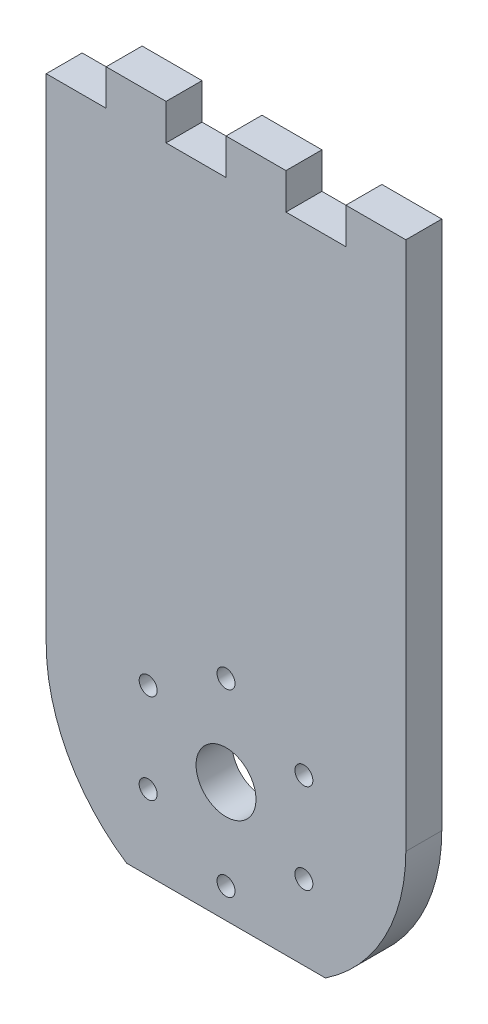
SolidWorks part; units mm, degrees
ref_plane "Alzado" through (0, 0, 0) normal (0, 0, 1) x (1, 0, 0)
ref_plane "Planta" through (0, 0, 0) normal (0, 1, 0) x (1, 0, 0)
ref_plane "Vista lateral" through (0, 0, 0) normal (1, 0, 0) x (0, 0, -1)
sketch "Croquis1" plane through (0, 0, 0) normal (0, 0, 1) x (1, 0, 0)
  line L0 (0, 28.345) -> (0, -18.345) construction
  line L1 (-15, -28.345) -> (15, -28.345)
  line L2 (-15, -28.345) -> (-15, 25.345)
  line L3 (-10, 28.345) -> (-5, 28.345)
  line L4 (15, -28.345) -> (15, 28.345)
  line L5 (-15, -28.345) -> (15, 28.345) construction
  line L6 (-15, 28.345) -> (15, -28.345) construction
  line L7 (-15, 25.345) -> (-10, 25.345)
  line L8 (-10, 25.345) -> (-10, 28.345)
  line L10 (-5, 28.345) -> (-5, 25.345)
  line L11 (-5, 25.345) -> (0, 25.345)
  line L12 (0, 25.345) -> (0, 28.345)
  line L14 (5, 28.345) -> (5, 25.345)
  line L15 (5, 25.345) -> (10, 25.345)
  line L16 (10, 25.345) -> (10, 28.345)
  line L17 (0, 28.345) -> (5, 28.345)
  line L18 (10, 28.345) -> (15, 28.345)
  line L19 (-15, -28.345) -> (-15, 28.345) construction
  line L20 (-15, 28.345) -> (15, 28.345) construction
  point P0 (0, 0)
  dimension "D2" = 56.69
  dimension "D3" = 5
  dimension "D1" = 46.69
  dimension "D4" = 30
  dimension "D5" = 5
  dimension "D6" = 3
  dimension "D7" = 5
  dimension "D8" = 5
extrude "Saliente-Extruir1" add sketch "Croquis1" along normal blind 3
sketch "Croquis2" plane through (0, 0, 0) normal (0, 0, -1) x (-1, 0, 0)
  line L0 (-15, -15.845) -> (-21.1868, -15.845)
  line L1 (-21.1868, -15.845) -> (-21.1868, -34.6481)
  line L2 (-21.1868, -34.6481) -> (21.189, -34.6481)
  line L3 (21.189, -34.6481) -> (21.189, -15.845)
  line L4 (21.189, -15.845) -> (15, -15.845)
  arc A0 (-15, -15.845) -> (15, -15.845) centre (0, -15.845) ccw
  point P5 (-21.1868, -25.2465)
  dimension "D1" = 30
  dimension "D2" = 18.8031
  dimension "D3" = 42.3757
  dimension "D4" = 6.1868
extrude "Cortar-Extruir1" cut sketch "Croquis2" against normal blind 3
sketch "Croquis3" plane through (0, 0, 0) normal (0, 0, -1) x (-1, 0, 0)
  line L0 (0, 28.345) -> (0, -18.345) construction
  line L1 (0, -18.345) -> (0, -10.845) construction
  circle A0 centre (0, -10.845) radius 0.75
  circle A1 centre (6.4952, -14.595) radius 0.75
  circle A2 centre (6.4952, -22.095) radius 0.75
  circle A3 centre (0, -25.845) radius 0.75
  circle A4 centre (-6.4952, -22.095) radius 0.75
  circle A5 centre (-6.4952, -14.595) radius 0.75
  circle A6 centre (0, -18.345) radius 7.5 construction
  circle A7 centre (0, -18.345) radius 2.5
  dimension "D2" = 7.5
  dimension "D3" = 1.5
  dimension "D6" = 15
  dimension "D7" = 5
  dimension "D1" = 46.69
  dimension "D5" = 7.5
  dimension "D4" = 6
extrude "Cortar-Extruir2" cut sketch "Croquis3" against normal up to next
